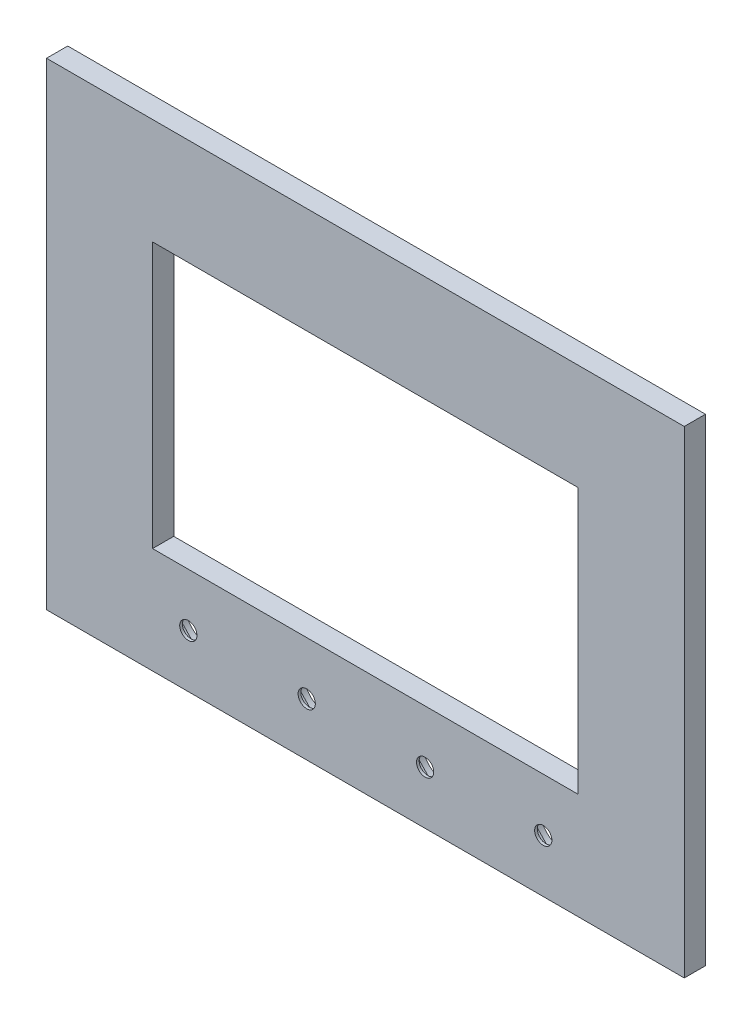
SolidWorks part; units mm, degrees
ref_plane "Front Plane" through (0, 0, 0) normal (0, 0, 1) x (1, 0, 0)
ref_plane "Top Plane" through (0, 0, 0) normal (0, 1, 0) x (1, 0, 0)
ref_plane "Right Plane" through (0, 0, 0) normal (1, 0, 0) x (0, 0, -1)
ref_plane "Plane1" through (0, 0, 0) normal (0, 0, -1) x (-1, 0, 0)
sketch "Sketch1" plane through (0, 0, 0) normal (0, 0, -1) x (-1, 0, 0)
  line L0 (69.5977, -77.75) -> (69.5977, 102.45)
  line L1 (69.5977, 102.45) -> (-171.0023, 102.45)
  line L2 (-171.0023, 102.45) -> (-171.0023, -77.75)
  line L3 (-171.0023, -77.75) -> (69.5977, -77.75)
extrude "Boss-Extrude1" add sketch "Sketch1" against normal blind 8
sketch "Sketch2" plane through (0, 0, 8) normal (0, 0, 1) x (1, 0, 0)
  line L0 (-29.5977, 62.45) -> (-29.5977, -37.75)
  line L1 (-29.5977, -37.75) -> (131.0023, -37.75)
  line L2 (131.0023, -37.75) -> (131.0023, 62.45)
  line L3 (131.0023, 62.45) -> (-29.5977, 62.45)
extrude "Cut-Extrude1" cut sketch "Sketch2" against normal through all
sketch "Sketch3" plane through (0, 0, 0) normal (0, 0, -1) x (-1, 0, 0)
  line L0 (-117.6868, -48.4833) -> (-127.0608, -58.1981)
  line L1 (-127.0608, -58.1981) -> (-117.9217, -67.0167)
  line L2 (-117.9217, -67.0167) -> (-108.5476, -57.3019)
  line L3 (-108.5476, -57.3019) -> (-117.6868, -48.4833)
extrude "Cut-Extrude2" cut sketch "Sketch3" against normal blind 7
sketch "Sketch4" plane through (0, 0, 0) normal (0, 0, -1) x (-1, 0, 0)
  line L0 (6.9392, -58.1981) -> (16.0783, -67.0167)
  line L1 (16.0783, -67.0167) -> (25.4524, -57.3019)
  line L2 (25.4524, -57.3019) -> (16.3132, -48.4833)
  line L3 (16.3132, -48.4833) -> (6.9392, -58.1981)
extrude "Cut-Extrude3" cut sketch "Sketch4" against normal blind 7
sketch "Sketch5" plane through (0, 0, 0) normal (0, 0, -1) x (-1, 0, 0)
  line L0 (-37.7275, -58.1981) -> (-28.5883, -67.0167)
  line L1 (-28.5883, -67.0167) -> (-19.2143, -57.3019)
  line L2 (-19.2143, -57.3019) -> (-28.3534, -48.4833)
  line L3 (-28.3534, -48.4833) -> (-37.7275, -58.1981)
extrude "Cut-Extrude4" cut sketch "Sketch5" against normal blind 7
sketch "Sketch6" plane through (0, 0, 0) normal (0, 0, -1) x (-1, 0, 0)
  line L0 (-82.3941, -58.1981) -> (-73.255, -67.0167)
  line L1 (-73.255, -67.0167) -> (-63.881, -57.3019)
  line L2 (-63.881, -57.3019) -> (-73.0201, -48.4833)
  line L3 (-73.0201, -48.4833) -> (-82.3941, -58.1981)
extrude "Cut-Extrude5" cut sketch "Sketch6" against normal blind 7
hole_wizard "Ø6.5 (6.5) Diameter Hole1" positions "Sketch8" profile "Sketch7" hole size "Ø6.5" standard "ANSI Metric"
sketch "Sketch8" plane through (0, 0, 8) normal (0, 0, 1) x (1, 0, 0)
  point P0 (117.8042, -57.75)
  point P1 (-16.0977, -57.75)
  point P2 (28.569, -57.75)
  point P3 (73.2357, -57.75)
sketch "Sketch7" plane through (117.8042, -57.75, 8) normal (1, 0, 0) x (0, -1, 0)
  line L0 (0, 0) -> (0, 8)
  line L1 (0, 8) -> (3.25, 8)
  line L2 (3.25, 8) -> (3.25, 0)
  line L5 (3.25, 0) -> (0, 0)
  line L11 (0, -6.35) -> (0, 107.95) construction
  dimension "Thru Hole Dia." = 6.5
  dimension "Thru Hole Depth" = 8
sketch "Sketch9" plane through (0, 0, 0) normal (0, 0, -1) x (-1, 0, 0)
  line L0 (-126.9808, -58.2753) -> (-117.9867, -66.9539)
  line L3 (-127.0608, -58.1981) -> (-117.9217, -67.0167) construction
  line L4 (-117.6868, -48.4833) -> (-108.5476, -57.3019)
  line L7 (-108.5476, -57.3019) -> (-117.6868, -48.4833) construction
  line L8 (-117.6868, -48.4833) -> (-127.0608, -58.1981) construction
  line L9 (-117.9217, -67.0167) -> (-108.5476, -57.3019) construction
  circle A0 centre (-117.8042, -57.75) radius 9.2674
  circle A1 centre (-73.2357, -57.75) radius 9.2692
  circle A2 centre (-28.569, -57.75) radius 9.2692
  circle A3 centre (16.0977, -57.75) radius 9.2667
  point P0 (-117.8042, -57.75)
  line M2 (-82.3941, -58.1981) -> (-73.0201, -48.4833)
  line M3 (-73.0201, -48.4833) -> (-63.881, -57.3019)
  line M4 (-63.881, -57.3019) -> (-73.255, -67.0167)
  line M5 (-73.255, -67.0167) -> (-82.3941, -58.1981)
  line M6 (-37.7275, -58.1981) -> (-28.3534, -48.4833)
  line M7 (-28.3534, -48.4833) -> (-19.2143, -57.3019)
  line M8 (-19.2143, -57.3019) -> (-28.5883, -67.0167)
  line M9 (-28.5883, -67.0167) -> (-37.7275, -58.1981)
  line M10 (6.9392, -58.1981) -> (16.3132, -48.4833)
  line M11 (16.3132, -48.4833) -> (25.4524, -57.3019)
  line M12 (25.4524, -57.3019) -> (16.0783, -67.0167)
  line M13 (16.0783, -67.0167) -> (6.9392, -58.1981)
  line M14 (-117.6868, -48.4833) -> (-108.5476, -57.3019)
  line M15 (-108.5476, -57.3019) -> (-117.9217, -67.0167)
  line M16 (-117.9217, -67.0167) -> (-127.0608, -58.1981)
  line M17 (-127.0608, -58.1981) -> (-117.6868, -48.4833)
extrude "Cut-Extrude7" cut sketch "Sketch9" against normal blind 4 contours A0 M14 | A0 M16 | A0 M17 | A0 M15 | A1 M2 M4 M5 | A1 M3 | A2 M6 M8 M9 | A2 M7 | A3 M10 M13 | A3 M12 | A3 M11
sketch "Sketch10" plane through (0, 0, 0) normal (0, 0, -1) x (-1, 0, 0)
  circle A0 centre (-127.0023, 69.25) radius 1.5
  circle A1 centre (29.9977, 69.25) radius 1.5
  circle A2 centre (29.9977, -45.75) radius 1.5
  circle A3 centre (-127.0023, -45.75) radius 1.5
